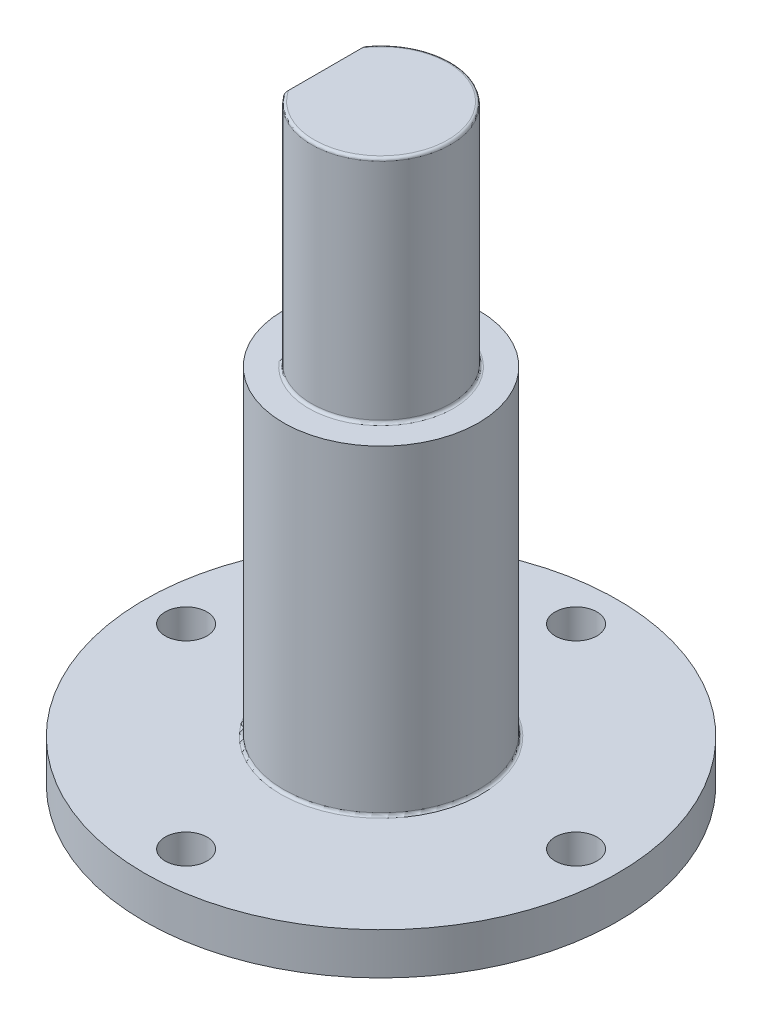
SolidWorks part; units mm, degrees
ref_plane "前视基准面" through (0, 0, 0) normal (0, 0, 1) x (1, 0, 0)
ref_plane "上视基准面" through (0, 0, 0) normal (0, 1, 0) x (1, 0, 0)
ref_plane "右视基准面" through (0, 0, 0) normal (1, 0, 0) x (0, 0, -1)
sketch "草图1" plane through (0, 0, 0) normal (0, 1, 0) x (1, 0, 0)
  circle A0 centre (0, 0) radius 17
  circle A1 centre (0, 0) radius 14 construction
  circle A2 centre (0, 14) radius 1.5
  circle A3 centre (14, 0) radius 1.5
  circle A4 centre (0, -14) radius 1.5
  circle A5 centre (-14, 0) radius 1.5
  point P15 (0, 0)
  dimension "D1" = 4
extrude "凸台-拉伸1" add sketch "草图1" along normal blind 3
sketch "草图2" plane through (0, 3, 0) normal (0, 1, 0) x (1, 0, 0)
  circle A0 centre (0, 0) radius 7
extrude "凸台-拉伸2" add sketch "草图2" along normal blind 23
sketch "草图3" plane through (0, 26, 0) normal (0, 1, 0) x (1, 0, 0)
  line L0 (0, 0) -> (-4, 0) construction
  line L1 (-4, 0) -> (-4, 3)
  line L2 (-4, 0) -> (-4, -3)
  arc A0 (-4, -3) -> (-4, 3) centre (0, 0) ccw
extrude "凸台-拉伸3" add sketch "草图3" along normal blind 16.5
fillet "圆角1" radius 0.2 3 edges at (5, 42.5, 0) (5, 26, 0) (0, 3, 7)
